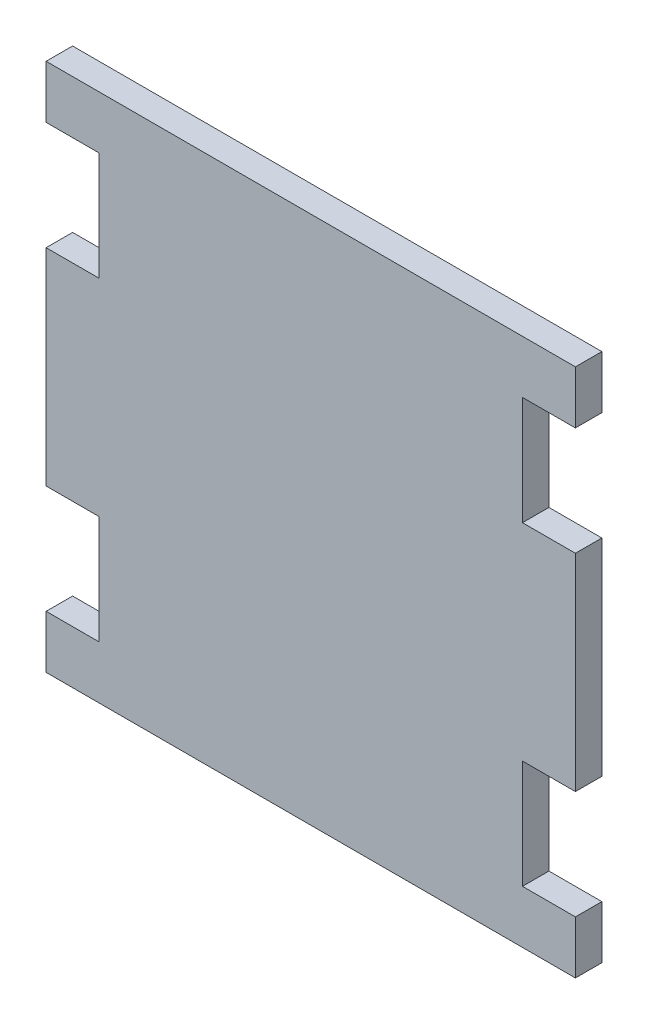
SolidWorks part; units mm, degrees
ref_plane "Plan de face" through (0, 0, 0) normal (0, 0, 1) x (1, 0, 0)
ref_plane "Plan de dessus" through (0, 0, 0) normal (0, 1, 0) x (1, 0, 0)
ref_plane "Plan de droite" through (0, 0, 0) normal (1, 0, 0) x (0, 0, -1)
sketch "Esquisse1" plane through (0, 0, 0) normal (0, 0, 1) x (1, 0, 0)
  line L1 (0, 0) -> (200, 0)
  line L2 (0, 0) -> (0, -200)
  line L3 (0, -200) -> (200, -200)
  line L4 (200, 0) -> (200, -200)
  dimension "D1" = 200
  dimension "D2" = 200
extrude "Boss.-Extru.1" add sketch "Esquisse1" along normal blind 10
sketch "Esquisse2" plane through (0, 0, 10) normal (0, 0, 1) x (1, 0, 0)
  line L0 (0, 0) -> (0, -200) construction
  line L1 (0, -20) -> (20, -20)
  line L2 (0, -20) -> (0, -61)
  line L3 (0, -61) -> (20, -61)
  line L4 (20, -20) -> (20, -61)
  line L5 (200, 0) -> (0, 0) construction
  line L6 (0, -200) -> (200, -200) construction
  line L7 (0, -180) -> (20, -180)
  line L8 (0, -180) -> (0, -139)
  line L9 (0, -139) -> (20, -139)
  line L10 (20, -180) -> (20, -139)
  line L11 (200, -200) -> (200, 0) construction
  line L12 (200, -20) -> (180, -20)
  line L13 (200, -20) -> (200, -61)
  line L14 (200, -61) -> (180, -61)
  line L15 (180, -20) -> (180, -61)
  line L17 (200, -139) -> (180, -139)
  line L18 (200, -139) -> (200, -180)
  line L19 (200, -180) -> (180, -180)
  line L20 (180, -139) -> (180, -180)
  dimension "D1" = 20
  dimension "D2" = 41
  dimension "D3" = 20
  dimension "D4" = 41
  dimension "D5" = 20
  dimension "D6" = 20
  dimension "D7" = 20
  dimension "D8" = 20
  dimension "D9" = 41
  dimension "D10" = 20
extrude "Enlèv. mat.-Extru.1" cut sketch "Esquisse2" against normal blind 10
